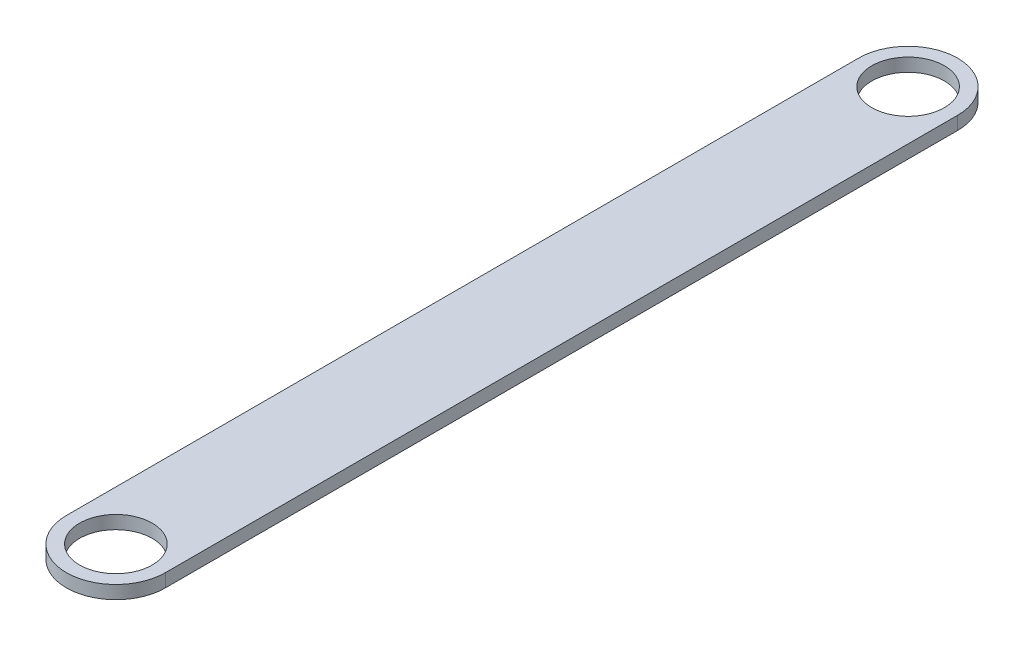
SolidWorks part; units mm, degrees
ref_plane "Front Plane" through (0, 0, 0) normal (0, 0, 1) x (1, 0, 0)
ref_plane "Top Plane" through (0, 0, 0) normal (0, 1, 0) x (1, 0, 0)
ref_plane "Right Plane" through (0, 0, 0) normal (1, 0, 0) x (0, 0, -1)
sketch "Sketch1" plane through (0, 0, 0) normal (0, 1, 0) x (1, 0, 0)
  line L0 (0, 0) -> (0, 120) construction
  line L1 (-7.5, 0) -> (-7.5, 120)
  line L2 (7.5, 0) -> (7.5, 120)
  arc A0 (-7.5, 0) -> (7.5, 0) centre (0, 0) ccw
  arc A1 (7.5, 120) -> (-7.5, 120) centre (0, 120) ccw
  circle A2 centre (0, 120) radius 5.5
  circle A3 centre (0, 0) radius 5.5
  point P3 (0, 60)
  dimension "D3" = 11
  dimension "D4" = 11
  dimension "D1" = 15
  dimension "D2" = 120
extrude "Boss-Extrude1" add sketch "Sketch1" along normal blind 2
